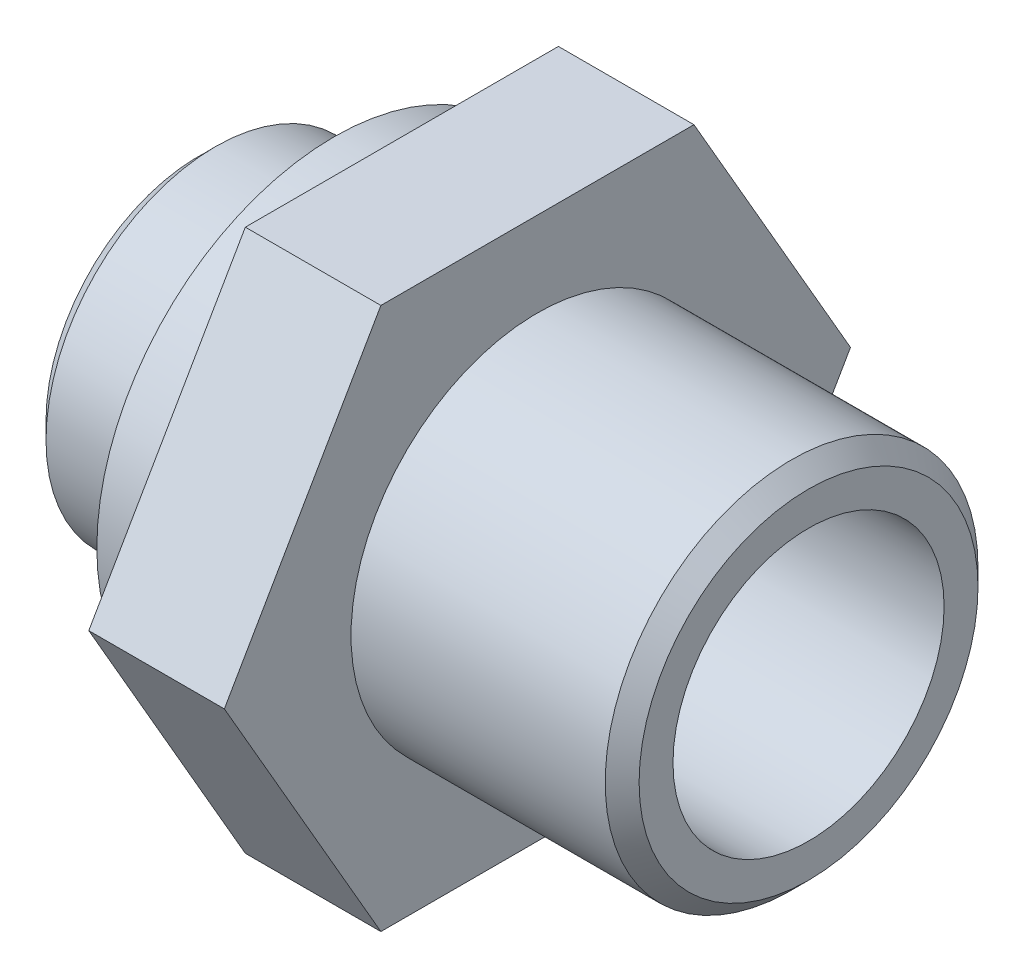
SolidWorks part; units mm, degrees
ref_plane "Front Plane" through (0, 0, 0) normal (0, 0, 1) x (1, 0, 0)
ref_plane "Top Plane" through (0, 0, 0) normal (0, 1, 0) x (1, 0, 0)
ref_plane "Right Plane" through (0, 0, 0) normal (1, 0, 0) x (0, 0, -1)
sketch "Sketch1" plane through (0, 0, 0) normal (1, 0, 0) x (0, 0, -1)
  circle A0 centre (0, 0) radius 2.75
  dimension "D1" = 5.5
extrude "Boss-Extrude1" add sketch "Sketch1" along normal blind 4
sketch "Sketch2" plane through (0, 0, 0) normal (-1, 0, 0) x (0, 0, 1)
  line L1 (2.3094, 4) -> (-2.3094, 4)
  line L2 (-2.3094, 4) -> (-4.6188, 0)
  line L3 (-4.6188, 0) -> (-2.3094, -4)
  line L4 (-2.3094, -4) -> (2.3094, -4)
  line L5 (2.3094, -4) -> (4.6188, 0)
  line L6 (4.6188, 0) -> (2.3094, 4)
  circle A0 centre (0, 0) radius 4 construction
  point P1 (0, 0)
  dimension "D1" = 8
extrude "Boss-Extrude2" add sketch "Sketch2" along normal blind 2
sketch "Sketch3" plane through (-2, 0, 0) normal (-1, 0, 0) x (0, 0, 1)
  circle A0 centre (0, 0) radius 3.5
  dimension "D1" = 7
extrude "Boss-Extrude3" add sketch "Sketch3" along normal blind 1
sketch "Sketch4" plane through (-3, 0, 0) normal (-1, 0, 0) x (0, 0, 1)
  circle A0 centre (0, 0) radius 2.5
  dimension "D1" = 5
extrude "Boss-Extrude4" add sketch "Sketch4" along normal blind 2
sketch "Sketch5" plane through (-5, 0, 0) normal (-1, 0, 0) x (0, 0, 1)
  circle A0 centre (0, 0) radius 2
  dimension "D1" = 4
extrude "Cut-Extrude1" cut sketch "Sketch5" against normal through all
chamfer "Chamfer1" distance 0.25 angle 45 2 edges at (4, 0, -2.75) (-5, 0, 2.5)
